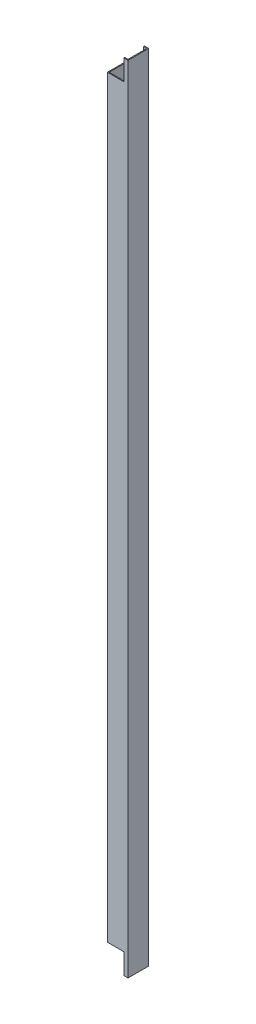
SolidWorks part; units mm, degrees
ref_plane "Front Plane" through (0, 0, 0) normal (0, 0, 1) x (1, 0, 0)
ref_plane "Top Plane" through (0, 0, 0) normal (0, 1, 0) x (1, 0, 0)
ref_plane "Right Plane" through (0, 0, 0) normal (1, 0, 0) x (0, 0, -1)
sketch "Sketch1" plane through (0, 0, 0) normal (0, 1, 0) x (1, 0, 0)
  line L0 (0, 0) -> (0, 50)
  line L1 (0, 50) -> (50, 50)
  line L2 (50, 50) -> (50, 0)
  line L3 (50, 0) -> (0, 0)
  line L4 (2.2, 47.8) -> (47.8, 47.8)
  line L5 (47.8, 47.8) -> (47.8, 2.2)
  line L6 (47.8, 2.2) -> (2.2, 2.2)
  line L7 (2.2, 2.2) -> (2.2, 47.8)
  dimension "D1" = 50
  dimension "D2" = 50
  dimension "D3" = 2.2
extrude "Boss-Extrude1" add sketch "Sketch1" along normal blind 1923
sketch "Sketch2" plane through (0, 0, 0) normal (0, 0, 1) x (1, 0, 0)
  line L0 (0, 0) -> (0, 50)
  line L1 (0, 1923) -> (0, 0) construction
  line L2 (0, 50) -> (40, 50)
  line L3 (40, 50) -> (40, 0)
  line L5 (40, 0) -> (0, 0)
  line L6 (0, 1923) -> (40, 1923)
  line L7 (0, 1923) -> (50, 1923) construction
  line L8 (40, 1923) -> (40, 1873)
  line L9 (40, 1873) -> (0, 1873)
  line L10 (0, 1873) -> (0, 1923)
  dimension "D1" = 50
  dimension "D2" = 40
  dimension "D3" = 50
  dimension "D4" = 40
extrude "Cut-Extrude2" cut sketch "Sketch2" against normal blind 50
equation "\"SquareTube_length\"=1923.0"
equation "\"D1@Boss-Extrude1\"=\"SquareTube_length\""
equation "\"SquareTube_inFront1_cutDepth50_R\"=0.5"
equation "\"D1@Sketch2\" = \"SquareTube_inFront13_cutDepth50_R\""
equation "\"SquareTube_inFront1_cutDepth50_L\"=0.5"
equation "\"D3@Sketch2\" = \"SquareTube_inFront13_cutDepth50_L\""
equation "\"CarBeamWidth\"=700.0"
equation "\"MetalSheet_3mm_length\"=5030.0"
equation "\"MetalSheet_3mm_width\"=1923.0"
equation "\"MetalSheet_3mm_FloorCut_L_length\"=1764.0"
equation "\"MetalSheet_3mm_FloorCut_L_disdance\"=1665.0"
equation "\"MetalSheet_3mm_FloorCut_R_length\"=1764.0"
equation "\"MetalSheet_3mm_FloorCut_R_disdance\"=1665.0"
equation "\"indoorHeight\"=1940.0"
equation "\"x\"=66.0"
equation "\"da\"=62.0"
equation "\"SquareTube_wheel_length\"= 750"
equation "\"channelSteel_length\"=5030.0"
equation "\"SquareTube_inFront2_cutDepth50_R\"=0.5"
equation "\"SquareTube_inFront2_cutDepth50_L\"=0.5"
equation "\"SquareTube_inFront3_cutDepth50_R\"=0.5"
equation "\"SquareTube_inFront3_cutDepth50_L\"=0.5"
equation "\"SquareTube_inFront4_cutDepth50_R\"=0.5"
equation "\"SquareTube_inFront4_cutDepth50_L\"=0.5"
equation "\"SquareTube_inFront5_cutDepth50_R\"=50"
equation "\"SquareTube_inFront5_cutDepth50_L\"=50"
equation "\"SquareTube_inFront6_cutDepth50_R\"=50"
equation "\"SquareTube_inFront6_cutDepth50_L\"=50"
equation "\"SquareTube_inFront7_cutDepth50_R\"=50"
equation "\"SquareTube_inFront7_cutDepth50_L\"=50"
equation "\"SquareTube_inFront8_cutDepth50_R\"=50"
equation "\"SquareTube_inFront8_cutDepth50_L\"=50"
equation "\"SquareTube_inFront9_cutDepth50_R\"=50"
equation "\"SquareTube_inFront9_cutDepth50_L\"=50"
equation "\"SquareTube_inFront10_cutDepth50_R\"=50"
equation "\"SquareTube_inFront10_cutDepth50_L\"=50"
equation "\"SquareTube_inBack1_cutDepth50_R\"=50"
equation "\"SquareTube_inBack1_cutDepth50_L\"=50"
equation "\"SquareTube_inBack2_cutDepth50_R\"=50"
equation "\"SquareTube_inBack2_cutDepth50_L\"=50"
equation "\"SquareTube_inBack3_cutDepth50_R\"=50"
equation "\"SquareTube_inBack3_cutDepth50_L\"=50"
equation "\"SquareTube_inBack4_cutDepth50_R\"=50"
equation "\"SquareTube_inBack4_cutDepth50_L\"=50"
equation "\"SquareTube_inBack5_cutDepth50_R\"=50"
equation "\"SquareTube_inBack5_cutDepth50_L\"=50"
equation "\"SquareTube_inBack6_cutDepth50_R\"=0.5"
equation "\"SquareTube_inBack6_cutDepth50_L\"=0.5"
equation "\"SquareTube_inFront11_cutDepth50_R\"=50"
equation "\"SquareTube_inFront11_cutDepth50_L\"=50"
equation "\"SquareTube_inFront12_cutDepth50_R\"=50"
equation "\"SquareTube_inFront12_cutDepth50_L\"=50"
equation "\"SquareTube_inFront13_cutDepth50_R\"=50"
equation "\"SquareTube_inFront13_cutDepth50_L\"=50"
equation "\"SquareTube_inFront14_cutDepth50_R\"=50"
equation "\"SquareTube_inFront14_cutDepth50_L\"=50"
equation "\"SquareTube_inBack7_cutDepth50_R\"=0.5"
equation "\"SquareTube_inBack7_cutDepth50_L\"=0.5"
equation "\"SquareTube_inBack8_cutDepth50_R\"=0.5"
equation "\"SquareTube_inBack8_cutDepth50_L\"=0.5"
